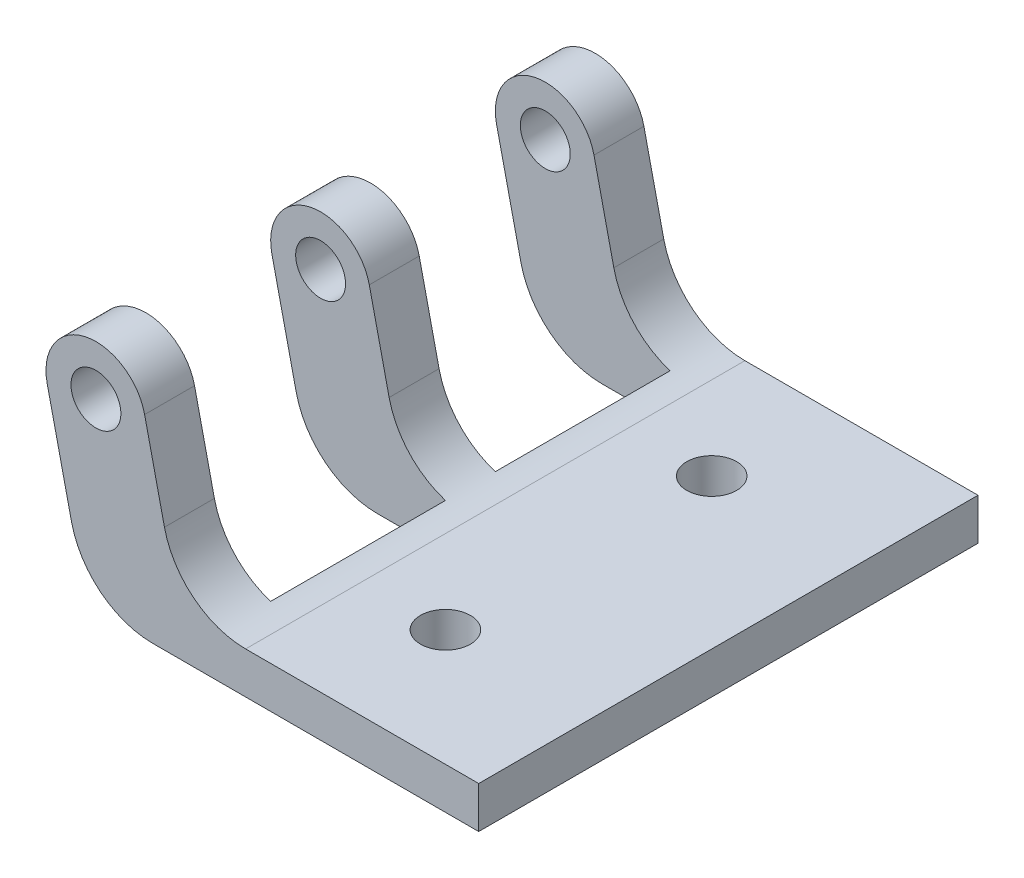
SolidWorks part; units mm, degrees
ref_plane "Plano frontal" through (0, 0, 0) normal (0, 0, 1) x (1, 0, 0)
ref_plane "Plano superior" through (0, 0, 0) normal (0, 1, 0) x (1, 0, 0)
ref_plane "Plano direito" through (0, 0, 0) normal (1, 0, 0) x (0, 0, -1)
sketch "Esboço1" plane through (0, 0, 0) normal (0, 0, 1) x (1, 0, 0)
  line L0 (-9, 0) -> (9, 0)
  line L1 (9, 0) -> (9, -2.5)
  line L2 (9, -2.5) -> (-14.5859, -2.5)
  line L3 (-14.5859, -2.5) -> (-16.926, 7.8377)
  line L4 (-9, 0) -> (-11.074, 9.1623)
  line L5 (10, -5.8654) -> (10, 13.9047) construction
  line L6 (-35, 68.0735) -> (7, 68.0735) construction
  line L7 (-35, 68.0735) -> (-35, 26.0735) construction
  line L8 (-35, 26.0735) -> (7, 26.0735) construction
  line L9 (7, 68.0735) -> (7, 26.0735) construction
  line L10 (-35, 68.0735) -> (7, 26.0735) construction
  line L11 (-35, 26.0735) -> (7, 68.0735) construction
  line L12 (-7.5, 47.0735) -> (-7.5, 8.5) construction
  circle A0 centre (-14, 8.5) radius 1.5
  arc A1 (-11.074, 9.1623) -> (-16.926, 7.8377) centre (-14, 8.5) ccw
  circle A2 centre (-14, 8.5) radius 6.5 construction
  circle A3 centre (-14, 47.0735) radius 6.5 construction
  point P7 (0, 0)
  point P11 (-14, 47.0735)
  dimension "D1" = 3
  dimension "D5" = 6
  dimension "D9" = 13
  dimension "D10" = 13
  dimension "D2" = 2.5
  dimension "D3" = 18
  dimension "D4" = 8.5
  dimension "D6" = 42
  dimension "D7" = 10
  dimension "D8" = 3
extrude "Ressalto-extrusão1" add sketch "Esboço1" along normal blind 30
fillet "Filete1" radius 5 2 edges at (-14.5859, -2.5, 15) (-9, 0, 15)
sketch "Esboço2" plane through (0, 0, 0) normal (0, 1, 0) x (1, 0, 0)
  line L0 (-17, 0) -> (-17, -30) construction
  line L1 (-17, -3) -> (-6.5, -3)
  line L2 (-17, -3) -> (-17, -13.5)
  line L3 (-17, -13.5) -> (-6.5, -13.5)
  line L4 (-6.5, -3) -> (-6.5, -13.5)
  line L7 (-17, -16.5) -> (-6.5, -16.5)
  line L8 (-17, -16.5) -> (-17, -27)
  line L9 (-17, -27) -> (-6.5, -27)
  line L10 (-6.5, -16.5) -> (-6.5, -27)
  line L12 (9, -15) -> (-18.9332, -15) construction
  line L13 (9, -30) -> (9, 0) construction
  circle A0 centre (0, -7) radius 1.5
  circle A1 centre (0, -23) radius 1.5
  dimension "D4" = 3
  dimension "D1" = 10.5
  dimension "D2" = 10.5
  dimension "D3" = 3
  dimension "D5" = 16
  dimension "D6" = 10.5
extrude "Corte-extrusão1" cut sketch "Esboço2" against normal through all both and the other way through all
